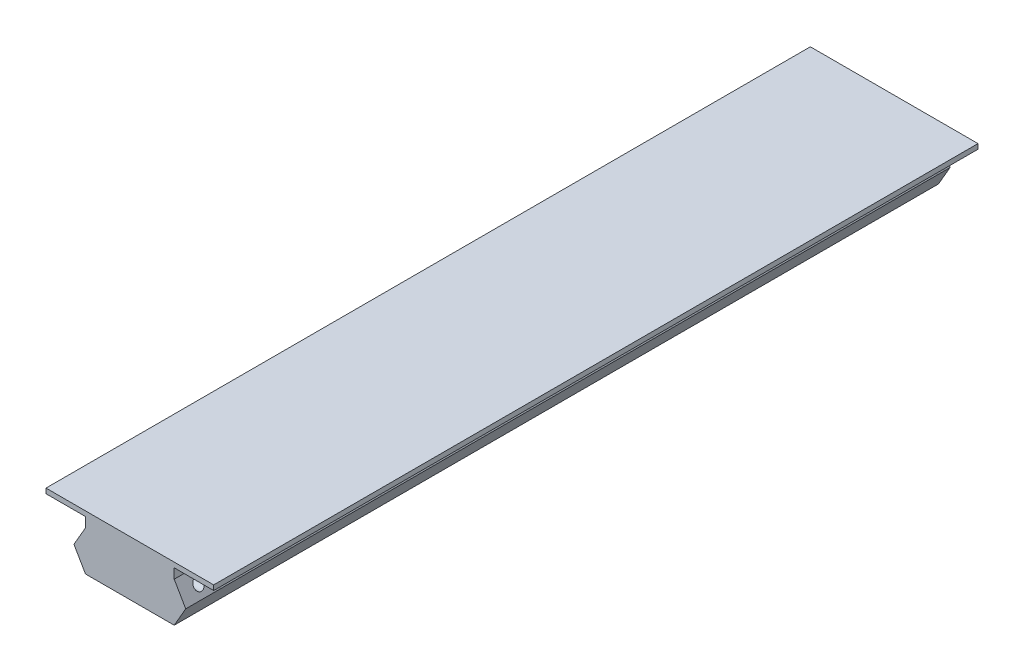
SolidWorks part; units mm, degrees
ref_plane "Front Plane" through (0, 0, 0) normal (0, 0, 1) x (1, 0, 0)
ref_plane "Top Plane" through (0, 0, 0) normal (0, 1, 0) x (1, 0, 0)
ref_plane "Right Plane" through (0, 0, 0) normal (1, 0, 0) x (0, 0, -1)
sketch "Sketch1" plane through (0, 0, 0) normal (0, 0, 1) x (1, 0, 0)
  line L0 (0, 0) -> (9.693, 0) construction
  line L1 (9.693, 0) -> (-8.307, 0)
  line L2 (-8.307, 0) -> (-10.642, 4.0443)
  line L3 (-10.642, 4.0443) -> (-8.307, 8.0887)
  line L5 (9.693, 8.0887) -> (12.028, 4.0443)
  line L6 (12.028, 4.0443) -> (9.693, 0)
  line L7 (-8.307, 8.0887) -> (-8.307, 10.0887)
  line L8 (-8.307, 10.0887) -> (-16.307, 10.0887)
  line L9 (-16.307, 10.0887) -> (-16.307, 11.0887)
  line L10 (-16.307, 11.0887) -> (17.693, 11.0887)
  line L11 (17.693, 11.0887) -> (17.693, 10.0887)
  line L12 (17.693, 10.0887) -> (9.693, 10.0887)
  line L13 (9.693, 10.0887) -> (9.693, 8.0887)
  dimension "D1" = 18
  dimension "D2" = 120
  dimension "D3" = 120
  dimension "D4" = 120
  dimension "D5" = 120
  dimension "D6" = 4.67
  dimension "D7" = 34
  dimension "D8" = 2
  dimension "D9" = 8
extrude "Boss-Extrude1" add sketch "Sketch1" against normal blind 155 contours L10 L11 L12 L13 L5 L6 L1 L2 L3 L7 L8 L9
sketch "Sketch2" plane through (0, 0, 0) normal (1, 0, 0) x (0, 0, -1)
  line L0 (155, 8.0887) -> (0, 8.0887) construction
  line L1 (0, 6.0988) -> (0, -6.0988) construction
  circle A0 centre (3.71, 5.9887) radius 1
  dimension "D1" = 2
  dimension "D2" = 2.1
  dimension "D3" = 3.71
extrude "Cut-Extrude1" cut sketch "Sketch2" against normal through all both and the other way through all
sketch "Sketch3" plane through (0, 0, 0) normal (1, 0, 0) x (0, 0, -1)
  line L0 (-5.5306, 10.7632) -> (49994.4694, 10.7632) construction
pattern_linear "LPattern1" count 41 spacing 3.71 along (0, 0, -1) of "Cut-Extrude1"
